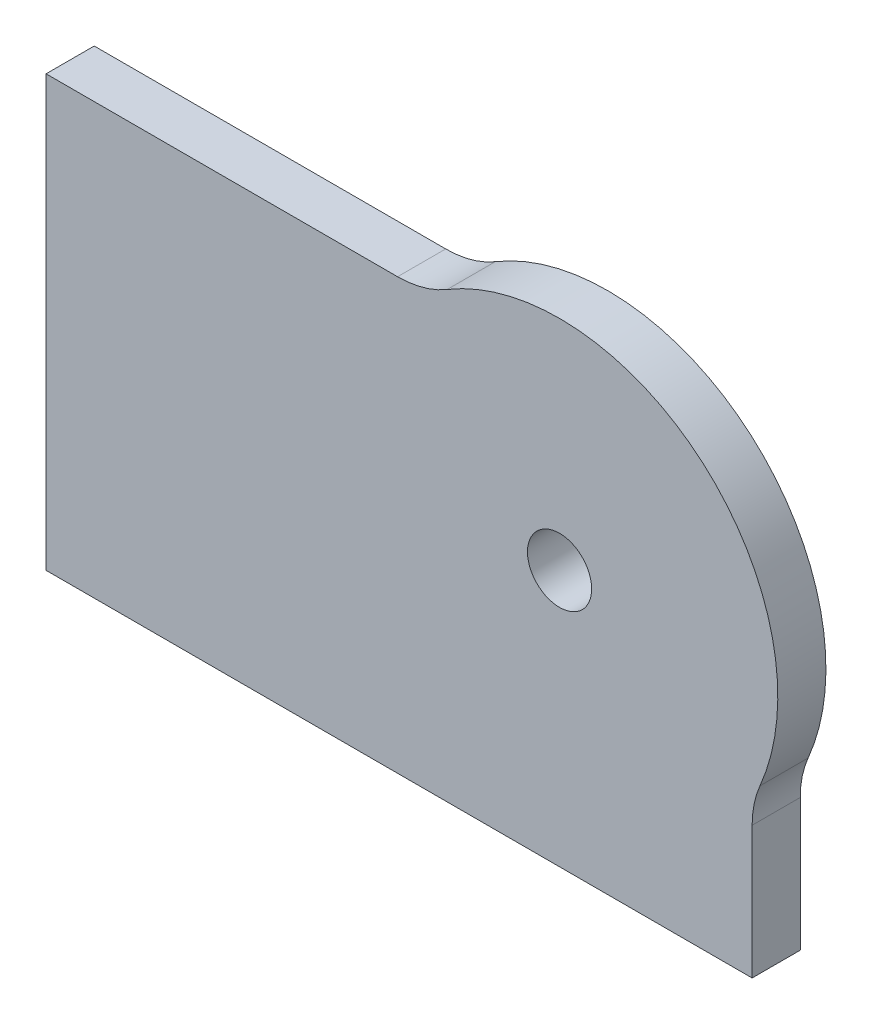
SolidWorks part; units mm, degrees
ref_plane "Front Plane" through (0, 0, 0) normal (0, 0, 1) x (1, 0, 0)
ref_plane "Top Plane" through (0, 0, 0) normal (0, 1, 0) x (1, 0, 0)
ref_plane "Right Plane" through (0, 0, 0) normal (1, 0, 0) x (0, 0, -1)
sketch "Sketch1" plane through (0, 0, 0) normal (0, 0, 1) x (1, 0, 0)
  line L0 (101.6, 50.8) -> (150.7534, 50.8) construction
  line L1 (0, 0) -> (139.7, 0)
  line L2 (0, 0) -> (0, 85.09)
  line L3 (0, 85.09) -> (69.5466, 85.09)
  line L4 (139.7, 0) -> (139.7, 26.1738)
  line L5 (101.6, 50.8) -> (123.597, 63.5) construction
  circle A0 centre (101.6, 50.8) radius 6.35
  arc A1 (141.2551, 33.7124) -> (79.3589, 87.8114) centre (101.6, 50.8) ccw
  arc A2 (69.5466, 85.09) -> (79.3589, 87.8114) centre (69.5466, 104.14) ccw
  arc A3 (139.7, 26.1738) -> (141.2551, 33.7124) centre (158.75, 26.1738) cw
  dimension "D5" = 19.05
  dimension "D6" = 25.4
  dimension "D8" = 12.7
  dimension "D1" = 139.7
  dimension "D2" = 85.09
  dimension "D3" = 101.6
  dimension "D4" = 50.8
  dimension "D7" = 30
extrude "Extrude1" add sketch "Sketch1" along normal blind 9.525
